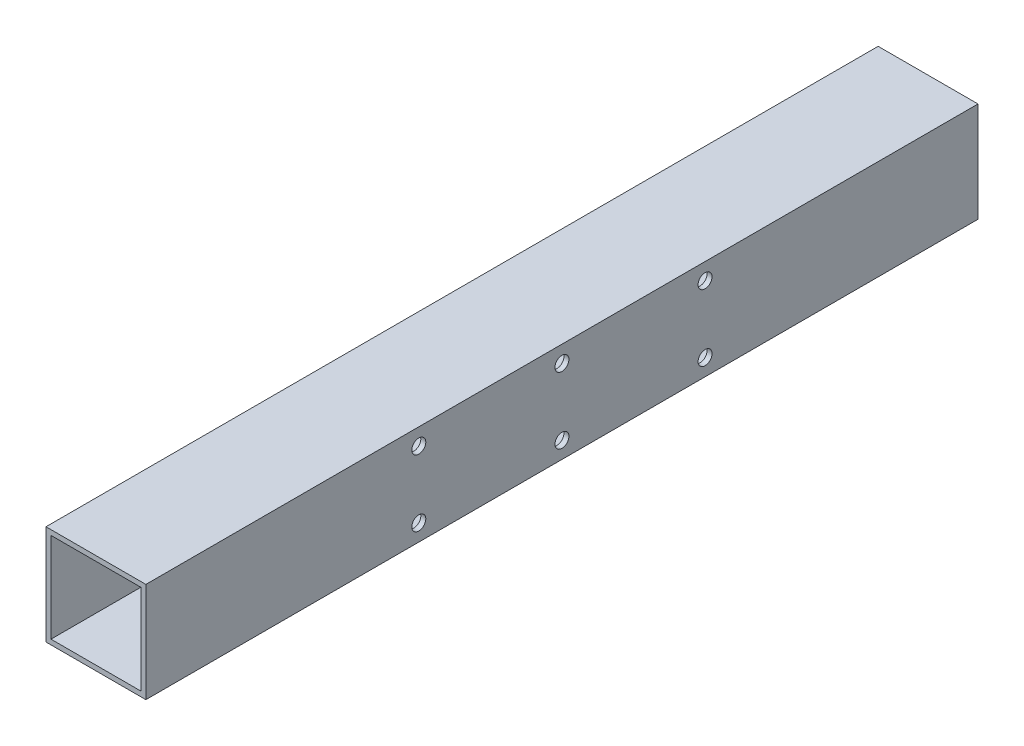
SolidWorks part; units mm, degrees
ref_plane "Front Plane" through (0, 0, 0) normal (0, 0, 1) x (1, 0, 0)
ref_plane "Top Plane" through (0, 0, 0) normal (0, 1, 0) x (1, 0, 0)
ref_plane "Right Plane" through (0, 0, 0) normal (1, 0, 0) x (0, 0, -1)
sketch "Sketch1" plane through (0, 0, 0) normal (0, 0, 1) x (1, 0, 0)
  line L1 (0, 0) -> (30, 0)
  line L2 (0, 0) -> (0, 30)
  line L3 (0, 30) -> (30, 30)
  line L4 (30, 0) -> (30, 30)
  line L5 (1.5, 1.5) -> (28.5, 1.5)
  line L6 (1.5, 1.5) -> (1.5, 28.5)
  line L7 (1.5, 28.5) -> (28.5, 28.5)
  line L8 (28.5, 1.5) -> (28.5, 28.5)
  point P9 (30, 15)
  dimension "D1" = 30
  dimension "D2" = 30
  dimension "D3" = 1.5
  dimension "D4" = 1.5
  dimension "D5" = 1.5
  dimension "D6" = 1.5
extrude "Boss-Extrude1" add sketch "Sketch1" along normal blind 250
sketch "Sketch2" plane through (0, 0, 0) normal (-1, 0, 0) x (0, 0, 1)
  line L0 (125, 30) -> (125, 0) construction
  line L1 (250, 30) -> (0, 30) construction
  line L2 (250, 0) -> (0, 0) construction
  circle A0 centre (125, 25) radius 2.1
  circle A1 centre (125, 5) radius 2.1
  circle A2 centre (168, 25) radius 2.1
  circle A3 centre (168, 5) radius 2.1
  circle A4 centre (82, 5) radius 2.1
  circle A5 centre (82, 25) radius 2.1
  dimension "D1" = 4.2
  dimension "D2" = 43
  dimension "D3" = 86
  dimension "D4" = 5
  dimension "D5" = 5
extrude "Cut-Extrude1" cut sketch "Sketch2" against normal through all
